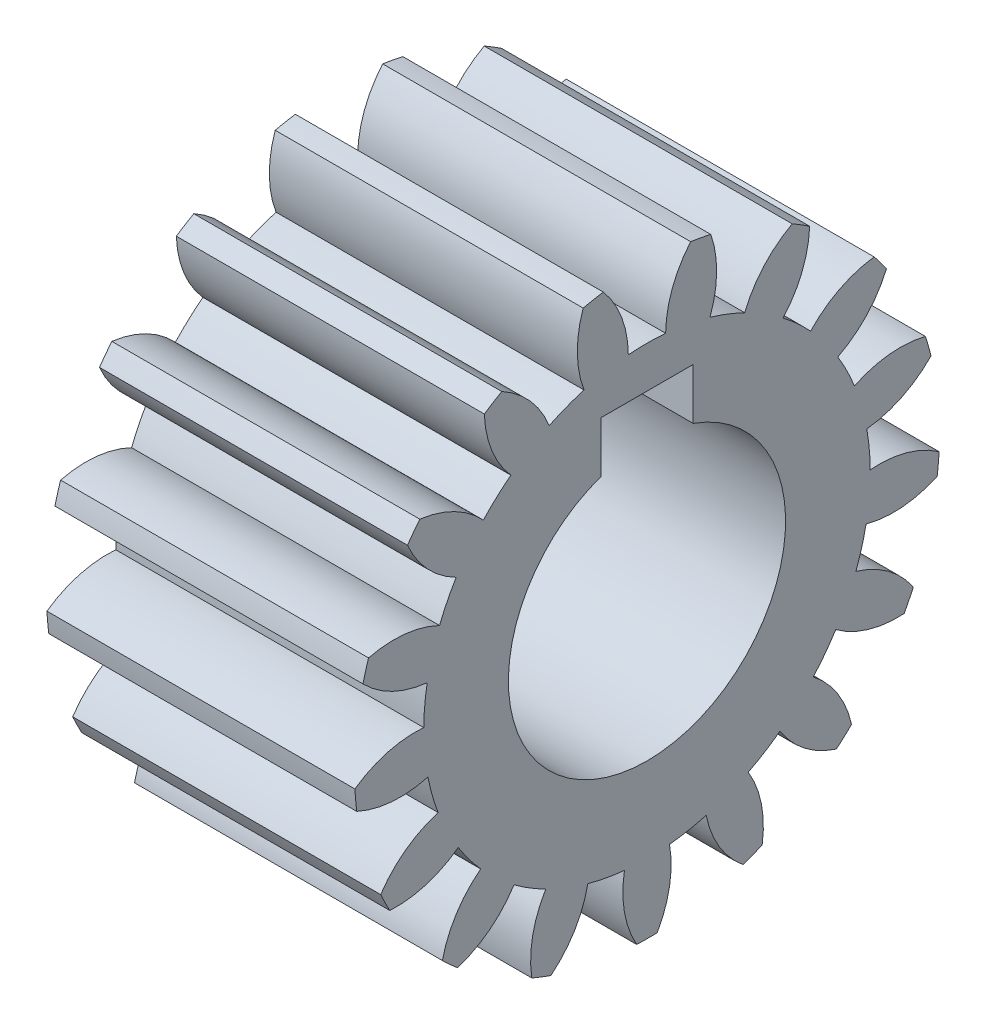
SolidWorks part; units mm, degrees
ref_plane "Plane1" through (0, 0, 0) normal (0, 0, 1) x (1, 0, 0)
ref_plane "Plane2" through (0, 0, 0) normal (0, 1, 0) x (1, 0, 0)
ref_plane "Plane3" through (0, 0, 0) normal (1, 0, 0) x (0, 0, -1)
sketch "HoldingSke" plane through (0, 0, 0) normal (0, 1, 0) x (1, 0, 0)
  line L0 (0, 0) -> (0.9563, -0.2924)
  line L1 (-15, 0) -> (100, 0) construction
  line L2 (0, 0) -> (-2.1039, 2.3779)
  line L3 (0, 0) -> (-11.863, 4.5341)
  line L4 (0, 0) -> (8.2586, 2.5249)
  line L5 (0, 0) -> (-46.8476, -17.4728)
  line L6 (0, 0) -> (-8.2896, -5.593)
  line L7 (-2.1039, 2.3779) -> (8.6586, 51.2059)
  line L8 (-76.2, 54.61) -> (-74.8, 54.61)
  line L9 (-67.7845, 28.3722) -> (-49.3413, 33.142)
  line L10 (-76.2, 71.12) -> (104.1128, 71.12)
  line L11 (0, 0) -> (-10, 0)
  line L12 (-76.2, 101.6) -> (-76.162, 101.6)
  line L13 (24.9733, 27.94) -> (52.9518, 28.4284)
  line L14 (24.9733, 27.94) -> (24.9743, 27.94)
  line L15 (24.9733, 27.94) -> (100.4006, 29.5858)
  line L16 (-63.627, -1) -> (-12.827, -1)
  circle A0 centre (0, 0) radius 4.5
  circle A1 centre (0, 0) radius 7.249
  circle A2 centre (0, 0) radius 37.5
  circle A3 centre (0, 0) radius 4.5
  dimension "MHD" = 14.498
  dimension "Hub_dia" = 75
  dimension "Bore" = 9
  dimension "MBD" = 9
  dimension "Num_teeth" = 17
  dimension "Pitch" = 1
  dimension "Overall_len" = 50
  dimension "Show_teeth" = 17
  dimension "Thickness" = 10
  dimension "OAL" = 50.0001
  dimension "T_dim" = 1.4
  dimension "Ap" = 14.5
  dimension "H" = 19.05
  dimension "Pitch_radius" = 180.3128
  dimension "Width" = 10
  dimension "Backlash" = 0.038
  dimension "Addendum_fac" = 1
  dimension "Dedendum_fac" = 1.25
  dimension "Clearance_fac" = 0.25
  dimension "Dedendum_add" = 0.001
  dimension "Module" = 1
sketch "BasProSke" plane through (0, 0, 0) normal (0, 1, 0) x (1, 0, 0)
  line L0 (-10, 0) -> (60, 0) construction
  line L1 (0, 0) -> (0, 9.5)
  line L2 (0, 0) -> (10, 0)
  line L3 (10, 0) -> (10, 9.5)
  line L4 (10, 9.5) -> (0, 9.5)
  dimension "Thickness" = 10
  dimension "Diameter" = 19
revolve "Base-Revolve" add sketch "BasProSke" angle 360 about L0
sketch "TooCutSke" plane through (0, 0, 0) normal (1, 0, 0) x (0, 0, -1)
  line L1 (0, 0) -> (0, 107) construction
  line L2 (0, 0) -> (-0.8507, 8.4573) construction
  line L3 (0, 0) -> (-3.1126, 16.6509) construction
  line L4 (-0.8507, 8.4573) -> (-1.5563, 8.3254) construction
  arc A0 (0.6054, 7.2237) -> (-0.6054, 7.2237) centre (0, 0) ccw
  arc A1 (1.4366, 9.4164) -> (-1.4366, 9.4164) centre (0, 0) ccw
  circle A2 centre (0, 0) radius 8.5 construction
  circle A3 centre (0, 0) radius 8.2293 construction
  arc A4 (-0.6054, 7.2237) -> (-1.4366, 9.4164) centre (-4.0052, 7.1888) ccw
  arc A5 (1.4366, 9.4164) -> (0.6054, 7.2237) centre (4.0052, 7.1888) ccw
  dimension "Root_dia" = 14.498
  dimension "Overcut_dia" = 19.0508
  dimension "Pitch_dia" = 17
  dimension "Base_dia" = 16.4585
  dimension "Flank_rad" = 3.4
  dimension "Half_ang" = 10.588
  dimension "Half_CT" = 0.7178
extrude "ToothCut" cut sketch "TooCutSke" along normal through all
fillet "Breaks" [suppressed] radius 0.02
fillet "RootFillets" [suppressed] radius 0.251
pattern_circular "TeethCuts" count 17 every 21.176 about axis through (-10, 0, 0) along (1, 0, 0) of "ToothCut", "RootFillets", "Breaks"
sketch "HubNeaOneSke" plane through (0, 0, 0) normal (-1, 0, 0) x (0, 0, 1)
  circle A0 centre (0, 0) radius 7.249
  dimension "Diameter" = 14.498
extrude "HubNearOne" [suppressed] add sketch "HubNeaOneSke" along normal blind 40.0001
sketch "HubNeaBotSke" plane through (0, 0, 0) normal (-1, 0, 0) x (0, 0, 1)
  circle A0 centre (0, 0) radius 7.249
  dimension "Diameter" = 14.498
extrude "HubNearBoth" [suppressed] add sketch "HubNeaBotSke" along normal blind 20
ref_plane "FarPln" through (10, 0, 0) normal (1, 0, 0) x (0, 0, -1)
sketch "HubFarSke" plane through (10, 0, 0) normal (1, 0, 0) x (0, 0, -1)
  circle A0 centre (0, 0) radius 7.249
  dimension "Diameter" = 14.498
extrude "HubFar" [suppressed] add sketch "HubFarSke" along normal blind 20
sketch "BorSke" plane through (0, 0, 0) normal (1, 0, 0) x (0, 0, -1)
  circle A0 centre (0, 0) radius 4.5
  dimension "Diameter" = 9
extrude "Bore" cut sketch "BorSke" along normal mid plane 100.0001
sketch "KeySke" plane through (0, 0, 0) normal (1, 0, 0) x (0, 0, -1)
  line L0 (-1.5, 0) -> (-1.5, 5.9)
  line L1 (-1.5, 5.9) -> (1.5, 5.9)
  line L2 (1.5, 5.9) -> (1.5, 0)
  line L3 (0, 0) -> (0, 34) construction
  line L4 (-1.5, 0) -> (1.5, 0)
  dimension "Offset" = 5.9
  dimension "Width" = 3
extrude "Keyway" cut sketch "KeySke" along normal mid plane 100.0001
pattern_circular "Keyway2" [suppressed] count 2 every 90 about axis through (-10, 0, 0) along (1, 0, 0)
equation "' \"Module@HoldingSke\" = 6.35"
equation "' \"Num_teeth@HoldingSke\" = 12"
equation "' \"Ap@HoldingSke\" =  20"
equation "' \"Ap@HoldingSke\" = 20"
equation "' \"Width@HoldingSke\" = 0.5 * 25.4"
equation "' \"Hub_dia@HoldingSke\"= 1 * 25.4"
equation "' \"Hub_dia@HoldingSke\" = 1 * 25.4"
equation "' \"Overall_len@HoldingSke\" = 1.0 * 25.4"
equation "' \"Bore@HoldingSke\" = 0.75 * 25.4"
equation "' \"T_dim@HoldingSke\" = 0.1 * 25.4"
equation "' \"Width@KeySke\" = 0.25 * 25.4"
equation "' \"Show_teeth@HoldingSke\" = 13"
equation "' \"Backlash@HoldingSke\" = 0.009 * 25.4"
equation "' \"Addendum_fac@HoldingSke\" = 1.0"
equation "' \"Dedendum_fac@HoldingSke\" = 1.25"
equation "' \"Dedendum_add@HoldingSke\" = 0.00005 * 25.4"
equation "' \"Clearance_fac@HoldingSke\" = 0.25"
equation "\"Pitch@HoldingSke\" = 1 / \"Module@HoldingSke\""
equation "\"Overcut_dia@TooCutSke\" = (\"Num_teeth@HoldingSke\" + 2 * \"Addendum_fac@HoldingSke\") / \"Pitch@HoldingSke\" + 0.002 * 25.4"
equation "\"Pitch_dia@TooCutSke\" = \"Num_teeth@HoldingSke\" / \"Pitch@HoldingSke\""
equation "\"Base_dia@TooCutSke\" = \"Num_teeth@HoldingSke\" / \"Pitch@HoldingSke\" * cos((\"Ap@HoldingSke\"  * 3.14159265 / 180))"
equation "\"Root_dia@TooCutSke\" = (\"Num_teeth@HoldingSke\" + 2) / \"Pitch@HoldingSke\" - 2 * (\"Addendum_fac@HoldingSke\" + \"Dedendum_fac@HoldingSke\") / \"Pitch@HoldingSke\" - \"Dedendum_add@HoldingSke\" * 2"
equation "\"Half_ang@TooCutSke\" = 180 / \"Num_teeth@HoldingSke\""
equation "\"Half_CT@TooCutSke\" = \"Num_teeth@HoldingSke\" / \"Pitch@HoldingSke\" * sin((3.14159265 / 2 / \"Num_teeth@HoldingSke\")) / 2 - 7 * \"Backlash@HoldingSke\" / 4"
equation "\"Flank_rad@TooCutSke\" = \"Num_teeth@HoldingSke\" / \"Pitch@HoldingSke\" / 5"
equation "\"Radius@RootFillets\" = \"Clearance_fac@HoldingSke\" / \"Pitch@HoldingSke\" + \"Dedendum_add@HoldingSke\""
equation "\"Break_rad@Breaks\" = 0.02 / \"Pitch@HoldingSke\""
equation "\"Thickness@HoldingSke\" = \"Width@HoldingSke\""
equation "\"OAL@HoldingSke\" = \"Thickness@HoldingSke\""
equation "\"MHD@HoldingSke\" = (\"Num_teeth@HoldingSke\" + 2) / \"Pitch@HoldingSke\" - 2 * (\"Addendum_fac@HoldingSke\" + \"Dedendum_fac@HoldingSke\")  / \"Pitch@HoldingSke\" - \"Dedendum_add@HoldingSke\" * 2"
equation "\"MBD@HoldingSke\" = (\"Num_teeth@HoldingSke\" + 2) / \"Pitch@HoldingSke\" - 2 * (\"Addendum_fac@HoldingSke\" + \"Dedendum_fac@HoldingSke\")  / \"Pitch@HoldingSke\" - \"Dedendum_add@HoldingSke\" * 2 - 0.002 * 25.4"
equation "\"MHD@HoldingSke\" = ((sgn( \"MHD@HoldingSke\" - \"Hub_dia@HoldingSke\" )-1)*( \"MHD@HoldingSke\" - \"Hub_dia@HoldingSke\" ))/-2+ \"Hub_dia@HoldingSke\""
equation "\"MBD@HoldingSke\" = ((sgn( \"MBD@HoldingSke\" - \"Bore@HoldingSke\" )-1)*( \"MBD@HoldingSke\" - \"Bore@HoldingSke\" ))/-2+ \"Bore@HoldingSke\""
equation "\"OAL@HoldingSke\" = ((sgn( \"OAL@HoldingSke\" - \"Overall_len@HoldingSke\" )+1)*( \"OAL@HoldingSke\" - \"Overall_len@HoldingSke\" ))/2 + \"Overall_len@HoldingSke\" + 0.000002 * 25.4"
equation "\"Num_teeth@TeethCuts\" = int( \"Show_teeth@HoldingSke\" ) + 1"
equation "\"Num_teeth@TeethCuts\" = ((sgn( \"Num_teeth@TeethCuts\" - \"Num_teeth@HoldingSke\" )-1)*( \"Num_teeth@TeethCuts\" - \"Num_teeth@HoldingSke\" ))/-2+ \"Num_teeth@HoldingSke\""
equation "\"Num_teeth@TeethCuts\" = ((sgn( \"Num_teeth@TeethCuts\" - 2.0)+1)*( \"Num_teeth@TeethCuts\" - 2.0))/2 +2.0"
equation "\"Angle@TeethCuts\" = 360.0 / \"Num_teeth@HoldingSke\""
equation "\"Diameter@BasProSke\" = (\"Num_teeth@HoldingSke\" + 2 * \"Addendum_fac@HoldingSke\") / \"Pitch@HoldingSke\""
equation "\"Thickness@BasProSke\"  = \"Thickness@HoldingSke\""
equation "' \"Fillet_rad@BasProSke\" =  \"Thickness@HoldingSke\" * 0.05"
equation "' \"Fillet_rad@BasProSke\" = \"Thickness@HoldingSke\" * 0.05"
equation "\"MHD@HoldingSke\" = ((sgn( \"MHD@HoldingSke\" - \"Root_dia@TooCutSke\" )-1)*( \"MHD@HoldingSke\" - \"Root_dia@TooCutSke\" ))/-2+ \"Root_dia@TooCutSke\""
equation "\"Diameter@HubNeaOneSke\" = \"MHD@HoldingSke\""
equation "\"Length@HubNearOne\" = \"OAL@HoldingSke\" - \"Thickness@BasProSke\""
equation "\"Diameter@HubNeaBotSke\" = \"MHD@HoldingSke\""
equation "\"Length@HubNearBoth\" = ( \"OAL@HoldingSke\" - \"Thickness@BasProSke\" ) / 2.0"
equation "\"Thickness@FarPln\" = \"Thickness@BasProSke\""
equation "\"Diameter@HubFarSke\" = \"MHD@HoldingSke\""
equation "\"Length@HubFar\" = ( \"OAL@HoldingSke\" - \"Thickness@BasProSke\" ) / 2.0"
equation "\"Diameter@BorSke\" = \"MBD@HoldingSke\""
equation "\"D1@Bore\" = \"OAL@HoldingSke\" * 2.0"
equation "\"D1@Keyway\" = \"OAL@HoldingSke\" * 2.0"
equation "\"Offset@KeySke\" = \"T_dim@HoldingSke\" + \"MBD@HoldingSke\" / 2.0"
